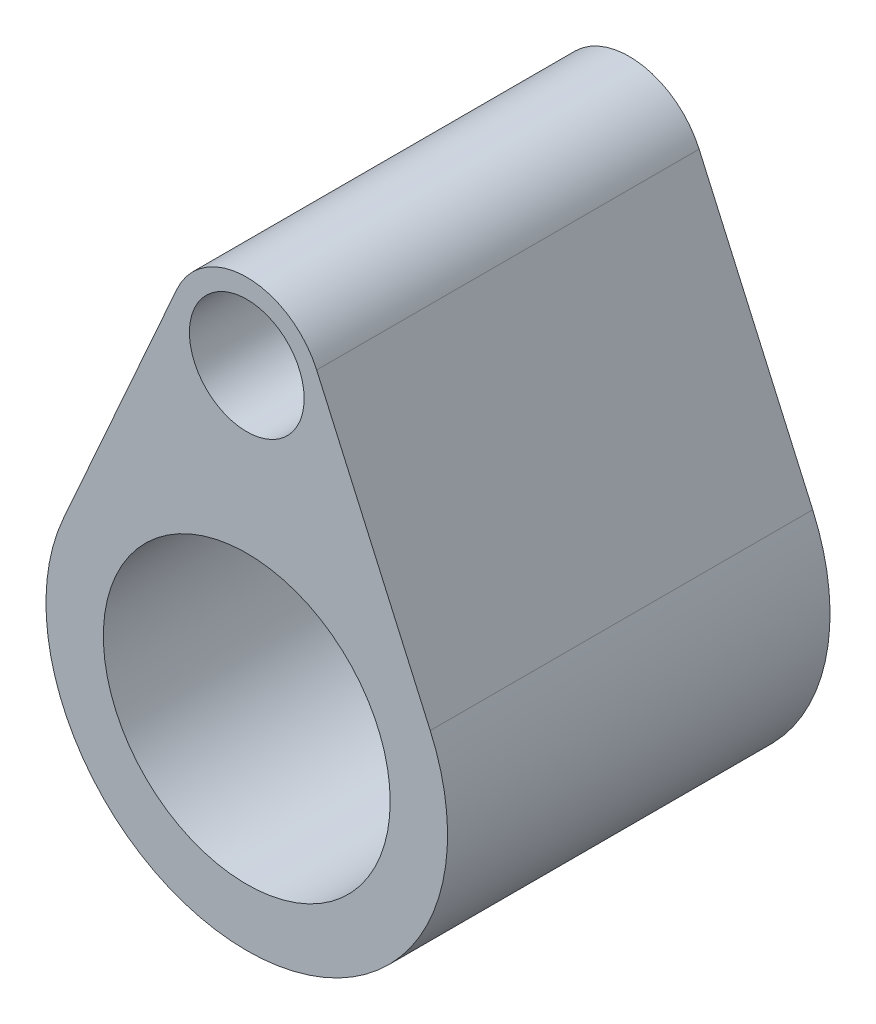
SolidWorks part; units mm, degrees
material "AISI 1020"
ref_plane "Front Plane" through (0, 0, 0) normal (0, 0, 1) x (1, 0, 0)
ref_plane "Top Plane" through (0, 0, 0) normal (0, 1, 0) x (1, 0, 0)
ref_plane "Right Plane" through (0, 0, 0) normal (1, 0, 0) x (0, 0, -1)
sketch "Sketch1" plane through (0, 0, 0) normal (0, 0, 1) x (1, 0, 0)
  line L0 (0, 0) -> (0, -160) construction
  line L1 (-95.945, -117.3438) -> (-36.5505, 16.25)
  line L2 (36.5505, 16.25) -> (95.945, -117.3438)
  circle A0 centre (0, 0) radius 25 construction
  arc A1 (36.5505, 16.25) -> (-36.5505, 16.25) centre (0, 0) ccw
  circle A2 centre (0, -160) radius 75
  arc A3 (-95.945, -117.3438) -> (95.945, -117.3438) centre (0, -160) ccw
  dimension "D1" = 160
  dimension "D2" = 50
  dimension "D3" = 150
  dimension "D4" = 30
  dimension "D5" = 15
extrude "Boss-Extrude1" add sketch "Sketch1" along normal mid plane 200
sketch "Sketch2" plane through (0, 0, 0) normal (0, 0, 1) x (1, 0, 0)
  line L4 (-22.844, 10.1562) -> (-82.2386, -123.4375)
  line L5 (-35.5292, -18.376) -> (-82.2386, -123.4375)
  line L7 (82.2386, -123.4375) -> (22.844, 10.1562)
  line L8 (82.2386, -123.4375) -> (35.5292, -18.376)
  arc A9 (36.5505, 16.25) -> (-36.5505, 16.25) centre (0, 0) ccw construction
  arc A10 (-35.5292, -18.376) -> (35.5292, -18.376) centre (0, 0) ccw
  circle A12 centre (0, -160) radius 90
  arc A13 (82.2386, -123.4375) -> (-82.2386, -123.4375) centre (0, -160) ccw
  dimension "D2" = 15
  dimension "D3" = 15
  dimension "D4" = 15
extrude "Cut-Extrude1" [suppressed] cut sketch "Sketch2" against normal through all both and the other way through all
fillet "Fillet1" [suppressed] radius 10
sketch "Sketch3" plane through (0, 0, 100) normal (0, 0, 1) x (1, 0, 0)
  circle A0 centre (0, 0) radius 30
  arc A1 (36.5505, 16.25) -> (-36.5505, 16.25) centre (0, 0) ccw construction
  dimension "D1" = 10
extrude "Cut-Extrude2" cut sketch "Sketch3" against normal through all
equation "\"A\"= 100"
equation "\"B\"= 100"
equation "\"C\"= 100"
equation "\"D\"= 100"
equation "\"E\"= 100"
